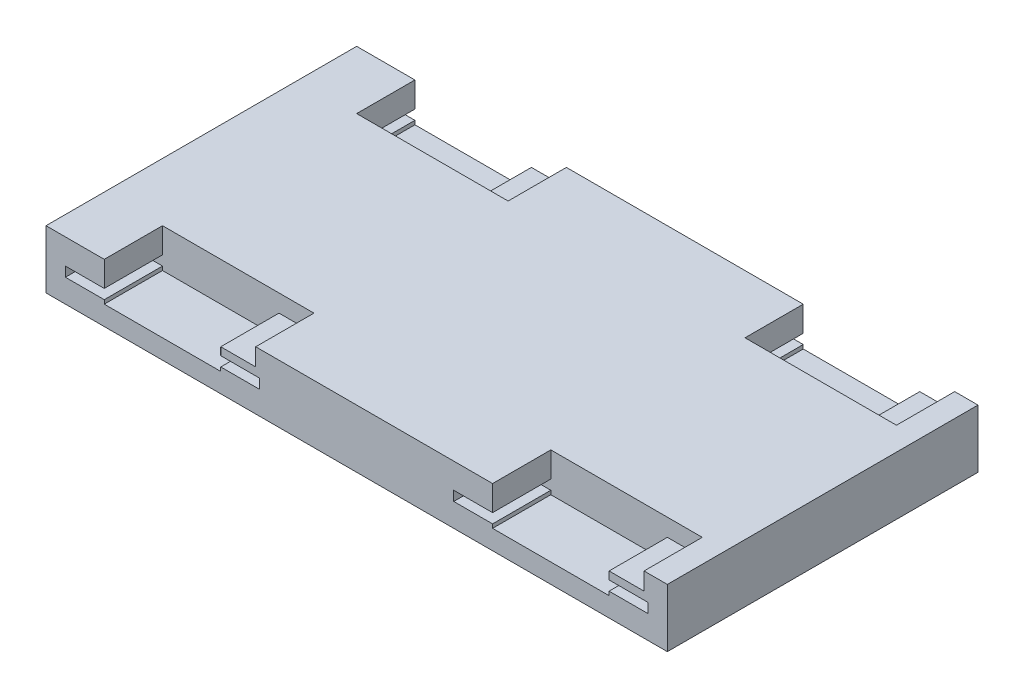
SolidWorks part; units mm, degrees
ref_plane "Front Plane" through (0, 0, 0) normal (0, 0, 1) x (1, 0, 0)
ref_plane "Top Plane" through (0, 0, 0) normal (0, 1, 0) x (1, 0, 0)
ref_plane "Right Plane" through (0, 0, 0) normal (1, 0, 0) x (0, 0, -1)
sketch "Sketch1" plane through (0, 0, 0) normal (0, 1, 0) x (1, 0, 0)
  line L1 (-160, 80) -> (160, 80)
  line L2 (-160, 80) -> (-160, -80)
  line L3 (-160, -80) -> (160, -80)
  line L4 (160, 80) -> (160, -80)
  line L5 (-160, 80) -> (160, -80) construction
  line L6 (-160, -80) -> (160, 80) construction
  point P0 (0, 0)
  dimension "D1" = 320
  dimension "D2" = 160
extrude "Boss-Extrude1" add sketch "Sketch1" along normal blind 20
sketch "Sketch2" plane through (0, 20, 0) normal (0, 1, 0) x (1, 0, 0)
  line L0 (-160, -80) -> (160, -80) construction
  line L1 (-130, -80) -> (-70, -80)
  line L2 (-130, -80) -> (-130, -50)
  line L3 (-130, -50) -> (-70, -50)
  line L4 (-70, -80) -> (-70, -50)
  line L5 (-160, 80) -> (-160, -80) construction
  dimension "D1" = 60
  dimension "D2" = 30
  dimension "D3" = 30
extrude "Cut-Extrude1" cut sketch "Sketch2" against normal blind 28
sketch "Sketch3" plane through (0, 0, 80) normal (0, 0, 1) x (1, 0, 0)
  line L0 (-130, 0) -> (-130, 20) construction
  line L1 (-130, 7) -> (-150, 7)
  line L2 (-130, 7) -> (-130, 2)
  line L3 (-130, 2) -> (-150, 2)
  line L4 (-150, 7) -> (-150, 2)
  line L5 (-160, 0) -> (-130, 0) construction
  line L6 (-70, 0) -> (-70, 20) construction
  line L7 (-70, 7) -> (-50, 7)
  line L8 (-70, 7) -> (-70, 2)
  line L9 (-70, 2) -> (-50, 2)
  line L10 (-50, 7) -> (-50, 2)
  line L11 (88, 0) -> (-88, 0) construction
  dimension "D1" = 2
  dimension "D2" = 5
  dimension "D3" = 20
  dimension "D4" = 20
  dimension "D5" = 5
  dimension "D6" = 2
extrude "Cut-Extrude3" cut sketch "Sketch3" against normal blind 30
mirror "Mirror2" about plane through (0, 0, 0) normal (1, 0, 0) of "Cut-Extrude1", "Cut-Extrude3"
mirror "Mirror3" about plane through (0, 0, 0) normal (0, 0, 1) of "Mirror2", "Cut-Extrude1", "Cut-Extrude3"
sketch "Sketch8" plane through (0, 0, -80) normal (0, 0, -1) x (-1, 0, 0)
  line L0 (-130, 7) -> (-130, 20) construction
  line L1 (-130, 11) -> (-148, 11)
  line L2 (-130, 11) -> (-130, 20)
  line L3 (-130, 20) -> (-148, 20)
  line L4 (-148, 11) -> (-148, 20)
  line L5 (-160, 20) -> (-130, 20) construction
  line L6 (-130, 7) -> (-150, 7) construction
  dimension "D1" = 18
  dimension "D2" = 4
extrude "Cut-Extrude6" cut sketch "Sketch8" against normal blind 30
sketch "Sketch9" plane through (0, 0, -80) normal (0, 0, -1) x (-1, 0, 0)
  line L0 (70, 20) -> (70, 7) construction
  line L1 (70, 11) -> (52, 11)
  line L2 (70, 11) -> (70, 20)
  line L3 (70, 20) -> (52, 20)
  line L4 (52, 11) -> (52, 20)
  line L5 (-70, 20) -> (70, 20) construction
  line L6 (50, 7) -> (70, 7) construction
  dimension "D1" = 18
  dimension "D2" = 4
extrude "Cut-Extrude7" cut sketch "Sketch9" against normal blind 30
sketch "Sketch10" plane through (0, 0, 0) normal (0, -1, 0) x (1, 0, 0)
  line L1 (-160, 80) -> (160, 80)
  line L2 (-160, 80) -> (-160, -80)
  line L3 (-160, -80) -> (160, -80)
  line L4 (160, 80) -> (160, -80)
extrude "Boss-Extrude2" add sketch "Sketch10" along normal blind 10
mirror "Mirror4" about plane through (0, 0, 0) normal (0, 0, 1) of "Cut-Extrude7", "Cut-Extrude6"
